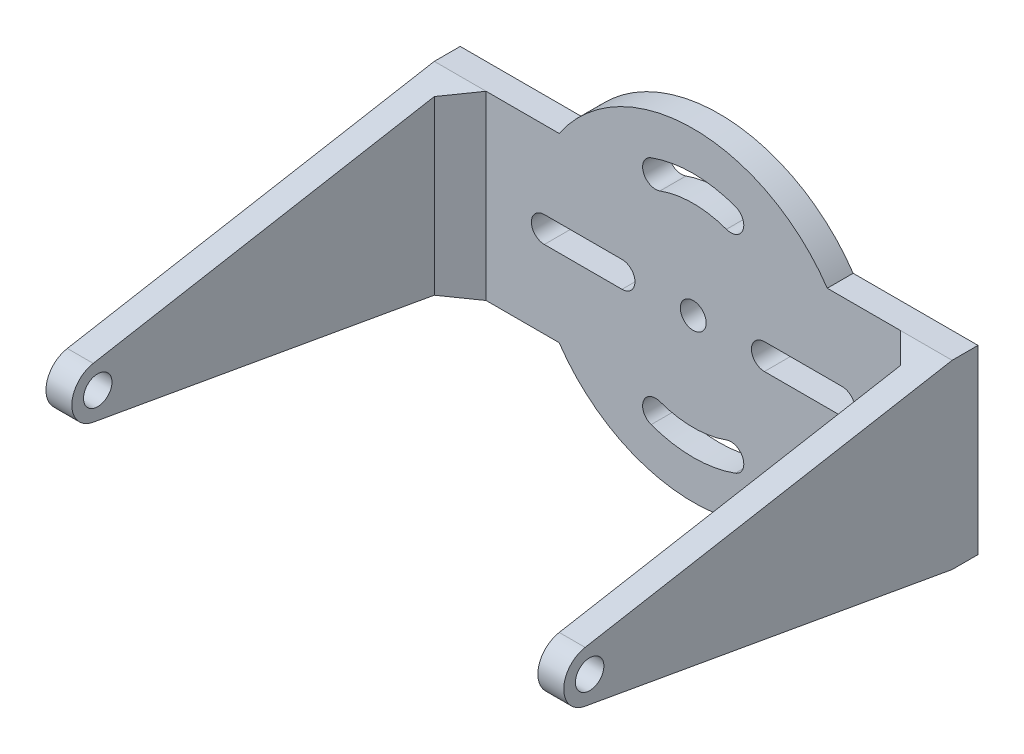
SolidWorks part; units mm, degrees
ref_plane "前视基准面" through (0, 0, 0) normal (0, 0, 1) x (1, 0, 0)
ref_plane "上视基准面" through (0, 0, 0) normal (0, 1, 0) x (1, 0, 0)
ref_plane "右视基准面" through (0, 0, 0) normal (1, 0, 0) x (0, 0, -1)
sketch "草图1" plane through (0, 0, 0) normal (0, 0, 1) x (1, 0, 0)
  line L1 (0, -990) -> (0, 49010) construction
  line L2 (10.3562, 7) -> (20, 7)
  line L3 (10.3562, 7) -> (10.3562, -7)
  line L4 (10.3562, -7) -> (20, -7)
  line L5 (20, 7) -> (20, -7)
  line L6 (-20, 7) -> (-20, -7)
  line L7 (-10.3562, -7) -> (-20, -7)
  line L8 (-10.3562, 7) -> (-20, 7)
  circle A0 centre (0, 0) radius 12.5
  dimension "D1" = 25
  dimension "D4" = 20
  dimension "D5" = 14
extrude "凸台-拉伸1" add sketch "草图1" along normal blind 2 contours A0 L8 L6 L7 | A0 L1 | L1 A0 L3 | L3 A0 | A0 L4 L5 L2
sketch "草图2" plane through (-20, 0, 0) normal (-1, 0, 0) x (0, 0, 1)
  line L0 (2, 7) -> (30.3495, 1.9692)
  line L1 (2, -7) -> (30.3495, -1.9692)
  line L2 (-998, 0) -> (49002, 0) construction
  line L3 (2, 7) -> (2, -7) construction
  line L4 (0, 7) -> (0, -7) construction
  arc A0 (30.3495, -1.9692) -> (30.3495, 1.9692) centre (30, 0) ccw
  circle A1 centre (30, 0) radius 1.1
  point P13 (2, 0)
  line M4 (2, -7) -> (2, 7)
  dimension "D2" = 4
  dimension "D3" = 2.2
  dimension "D1" = 30
extrude "凸台-拉伸2" add sketch "草图2" against normal blind 2 contours L2 L1 A0 A1 M4 | L2 A1 A0 L0 M4
mirror "镜向1" about plane through (0, 0, 0) normal (1, 0, 0) of "凸台-拉伸2"
sketch "草图3" plane through (0, 0, 2) normal (0, 0, 1) x (1, 0, 0)
  line L0 (0, 0) -> (-2.9072, 7.9874) construction
  line L1 (0, 8.5) -> (0, 0) construction
  line L2 (-11.5, 0) -> (-5.5, 0) construction
  line L3 (-11.5, 1) -> (-5.5, 1)
  line L4 (-11.5, -1) -> (-5.5, -1)
  circle A0 centre (0, 0) radius 8.5 construction
  circle A1 centre (0, 8.5) radius 1 construction
  circle A4 centre (-8.5, 0) radius 1 construction
  arc A5 (-2.9072, 7.9874) -> (2.9072, 7.9874) centre (0, 0) cw construction
  arc A6 (3.2492, 8.9271) -> (-3.2492, 8.9271) centre (0, 0) ccw
  arc A7 (2.5652, 7.0477) -> (-2.5652, 7.0477) centre (0, 0) ccw
  arc A8 (2.5652, 7.0477) -> (3.2492, 8.9271) centre (2.9072, 7.9874) ccw
  arc A9 (-3.2492, 8.9271) -> (-2.5652, 7.0477) centre (-2.9072, 7.9874) ccw
  arc A10 (-11.5, 1) -> (-11.5, -1) centre (-11.5, 0) ccw
  arc A11 (-5.5, -1) -> (-5.5, 1) centre (-5.5, 0) ccw
  circle A12 centre (0, 0) radius 1
  point P7 (0, 8.5)
  point P18 (-8.5, 0)
  dimension "D1" = 17
  dimension "D2" = 2
  dimension "D3" = 2
  dimension "D4" = 1
  dimension "D7" = 1
  dimension "D8" = 2
  dimension "D5" = 20
  dimension "D6" = 6
extrude "切除-拉伸1" cut sketch "草图3" against normal blind 2
mirror "镜向2" about plane through (0, 0, 0) normal (0, 1, 0) of "切除-拉伸1"
mirror "镜向3" about plane through (0, 0, 0) normal (1, 0, 0) of "切除-拉伸1"
chamfer "倒角1" distance 2 angle 45 2 edges at (18, 0, 2) (-18, 0, 2)
